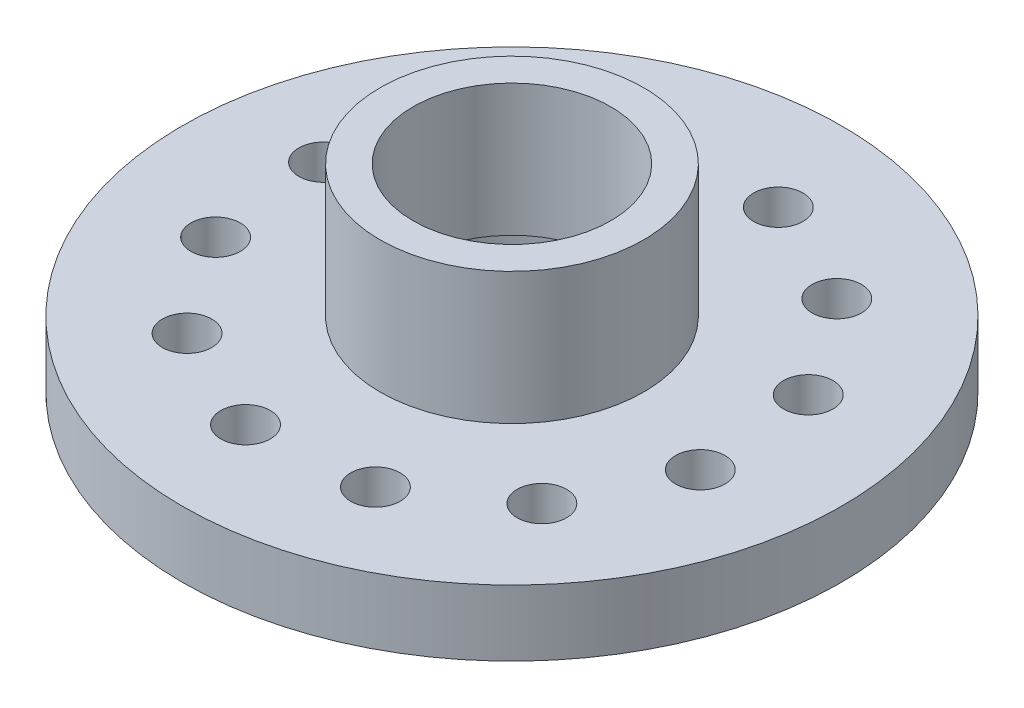
SolidWorks part; units mm, degrees
ref_plane "Front Plane" through (0, 0, 0) normal (0, 0, 1) x (1, 0, 0)
ref_plane "Top Plane" through (0, 0, 0) normal (0, 1, 0) x (1, 0, 0)
ref_plane "Right Plane" through (0, 0, 0) normal (1, 0, 0) x (0, 0, -1)
sketch "Sketch1" plane through (0, 0, 0) normal (0, 1, 0) x (1, 0, 0)
  circle A0 centre (0, 0) radius 10
  circle A1 centre (0, 0) radius 4
  dimension "D1" = 20
  dimension "D2" = 8
extrude "Boss-Extrude1" add sketch "Sketch1" along normal blind 2
sketch "Sketch2" plane through (0, 2, 0) normal (0, 1, 0) x (1, 0, 0)
  circle A0 centre (0, 0) radius 4 construction
  circle A1 centre (0, 0) radius 4
  circle A2 centre (0, 0) radius 3
  dimension "D1" = 6
extrude "Boss-Extrude2" add sketch "Sketch2" along normal blind 4 separate body
sketch "Sketch3" plane through (0, 2, 0) normal (0, 1, 0) x (1, 0, 0)
  circle A0 centre (-5.3831, 4.4746) radius 0.75
  circle A1 centre (-2.4246, 6.5667) radius 0.75
  circle A2 centre (1.1836, 6.8992) radius 0.75
  circle A3 centre (4.4746, 5.3831) radius 0.75
  circle A4 centre (6.5667, 2.4246) radius 0.75
  circle A5 centre (6.8992, -1.1836) radius 0.75
  circle A6 centre (5.3831, -4.4746) radius 0.75
  circle A7 centre (2.4246, -6.5667) radius 0.75
  circle A8 centre (-1.1836, -6.8992) radius 0.75
  circle A9 centre (-4.4746, -5.3831) radius 0.75
  circle A10 centre (-6.5667, -2.4246) radius 0.75
  circle A11 centre (-6.8992, 1.1836) radius 0.75
  point P27 (0, 0)
  dimension "D1" = 1.5
  dimension "D2" = 7
  dimension "D3" = 12
extrude "Cut-Extrude1" cut sketch "Sketch3" against normal through all
